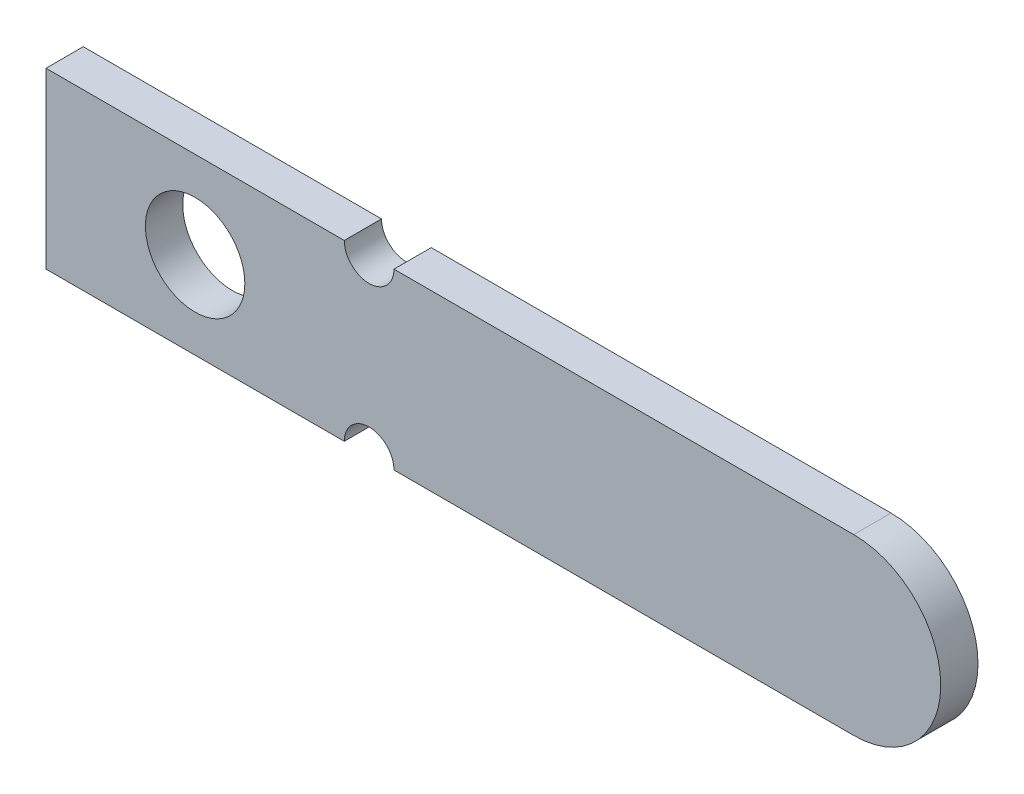
SolidWorks part; units mm, degrees
ref_plane "Front Plane" through (0, 0, 0) normal (0, 0, 1) x (1, 0, 0)
ref_plane "Top Plane" through (0, 0, 0) normal (0, 1, 0) x (1, 0, 0)
ref_plane "Right Plane" through (0, 0, 0) normal (1, 0, 0) x (0, 0, -1)
sketch "Sketch1" plane through (0, 0, 0) normal (0, 0, 1) x (1, 0, 0)
  line L0 (-4.25, 3.5) -> (-4.25, -3.5) construction
  line L1 (-16.25, 3.5) -> (-4.25, 3.5)
  line L2 (-16.25, 3.5) -> (-16.25, -3.5)
  line L3 (-16.25, -3.5) -> (-4.25, -3.5)
  line L5 (-2.25, 3.5) -> (-2.25, -3.5) construction
  line L6 (-2.25, 3.5) -> (16.25, 3.5)
  line L7 (-2.25, -3.5) -> (16.25, -3.5)
  arc A0 (16.25, -3.5) -> (16.25, 3.5) centre (16.25, 0) ccw
  arc A1 (-4.25, 3.5) -> (-2.25, 3.5) centre (-3.25, 3.5) ccw
  arc A2 (-2.25, -3.5) -> (-4.25, -3.5) centre (-3.25, -3.5) ccw
  circle A3 centre (-10.25, 0) radius 2
  point P0 (0, 0)
  point P13 (0, 0)
  point P16 (0, 0)
  point P17 (-10.25, 3.5)
  dimension "D3" = 7
  dimension "D6" = 4
  dimension "D1" = 7
  dimension "D2" = 32.5
  dimension "D4" = 12
  dimension "D5" = 2
extrude "Boss-Extrude1" add sketch "Sketch1" along normal blind 1.5
